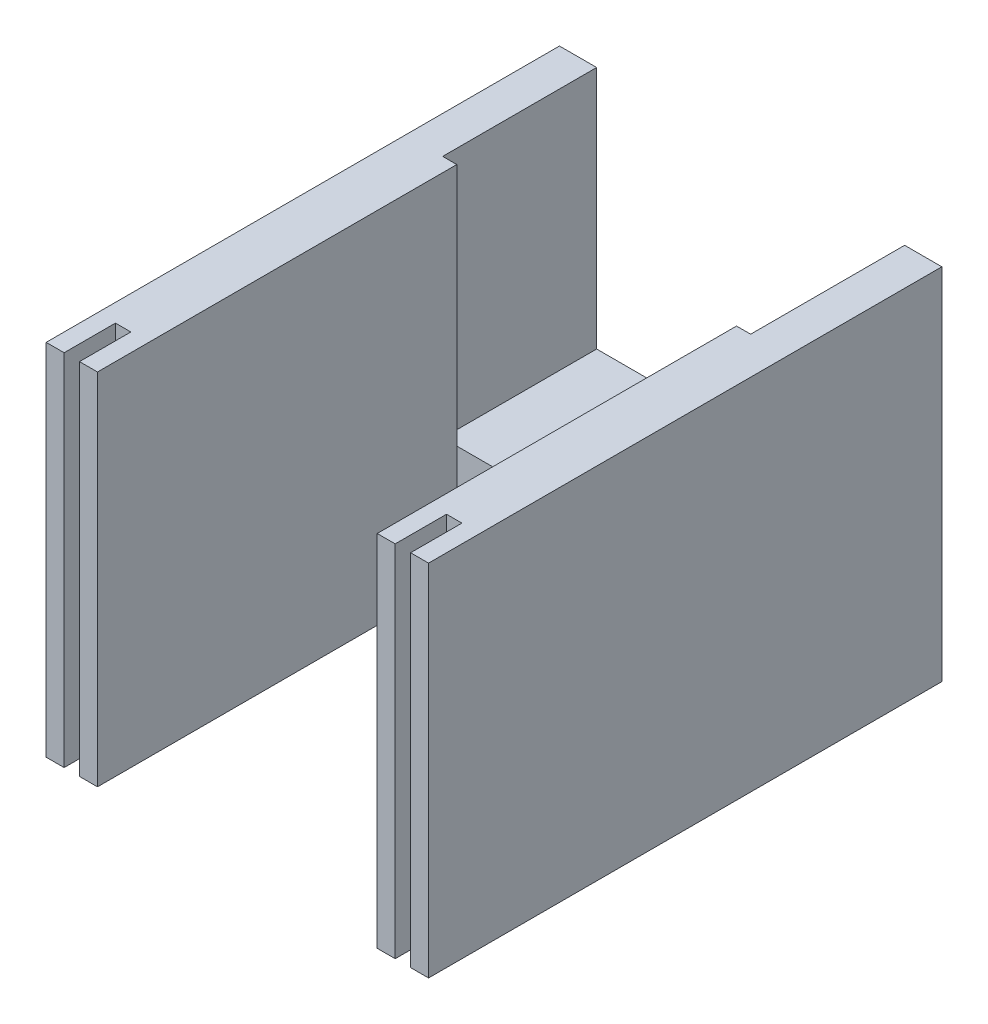
SolidWorks part; units mm, degrees
ref_plane "Front Plane" through (0, 0, 0) normal (0, 0, 1) x (1, 0, 0)
ref_plane "Top Plane" through (0, 0, 0) normal (0, 1, 0) x (1, 0, 0)
ref_plane "Right Plane" through (0, 0, 0) normal (1, 0, 0) x (0, 0, -1)
sketch "Sketch1" plane through (0, 0, 0) normal (0, 1, 0) x (1, 0, 0)
  line L1 (0, 0) -> (74.5, 0)
  line L2 (0, 0) -> (0, 100)
  line L3 (0, 100) -> (74.5, 100)
  line L4 (74.5, 0) -> (74.5, 100)
extrude "Boss-Extrude1" add sketch "Sketch1" along normal blind 70 contours L2 L3 L4 L1
sketch "Sketch3" plane through (0, 70, 0) normal (0, 1, 0) x (1, 0, 0)
  line L0 (74.5, 0) -> (57.5, 0)
  line L1 (0, 0) -> (74.5, 0) construction
  line L2 (0, 0) -> (10, 0)
  line L3 (0, 0) -> (10, 0)
  line L9 (10, 0) -> (64.5, 0)
  line L10 (10, 0) -> (10, 70)
  line L11 (10, 70) -> (64.5, 70)
  line L12 (64.5, 0) -> (64.5, 70)
  point P11 (0, 0)
extrude "Cut-Extrude1" cut sketch "Sketch3" against normal through all
ref_plane "Plane1" through (0, 70, -100) normal (1, 0, 0) x (0, 0, -1)
sketch "Sketch5" plane through (0, 70, 0) normal (0, 1, 0) x (1, 0, 0)
  line L0 (74.5, 100) -> (67.25, 100)
  line L1 (0, 100) -> (74.5, 100) construction
  line L2 (0, 100) -> (7.25, 100)
  line L3 (67.25, 100) -> (7.25, 100)
  line L4 (67.25, 100) -> (67.25, 70)
  line L5 (67.25, 70) -> (7.25, 70)
  line L6 (7.25, 100) -> (7.25, 70)
  point P9 (66.7211, 70.8322)
  line M13 (74.5, 100) -> (0, 100)
extrude "Cut-Extrude2" cut sketch "Sketch5" against normal blind 47.5 contours L6 L5 L4 M13
sketch "Sketch6" plane through (0, 70, 0) normal (0, 1, 0) x (1, 0, 0)
  line L0 (74.5, 0) -> (71, 0)
  line L1 (64.5, 0) -> (74.5, 0) construction
  line L2 (64.5, 0) -> (68, 0)
  line L4 (71, 0) -> (68, 0)
  line L5 (71, 0) -> (71, 10)
  line L6 (71, 10) -> (68, 10)
  line L7 (68, 0) -> (68, 10)
  line M11 (64.5, 0) -> (74.5, 0)
extrude "Cut-Extrude3" cut sketch "Sketch6" against normal through all contours L7 L5 L6 M11
sketch "Sketch7" plane through (0, 70, 0) normal (0, 1, 0) x (1, 0, 0)
  line L0 (10, 0) -> (6.5, 0)
  line L1 (0, 0) -> (10, 0) construction
  line L2 (0, 0) -> (3.5, 0)
  line L4 (6.5, 0) -> (3.5, 0)
  line L5 (6.5, 0) -> (6.5, 10)
  line L6 (6.5, 10) -> (3.5, 10)
  line L7 (3.5, 0) -> (3.5, 10)
  line M12 (0, 0) -> (10, 0)
extrude "Cut-Extrude4" cut sketch "Sketch7" against normal through all contours L7 L5 L6 M12
ref_plane "Plane2" through (64.5, 0, -70) normal (1, 0, 0) x (0, 0, -1)
sketch "Sketch10" plane through (0, 0, -100) normal (0, 0, -1) x (-1, 0, 0)
  line L0 (0, 0) -> (-74.5, 0) construction
  line L1 (-61.366, 0) -> (-10.6952, 0)
  line L2 (-61.366, 0) -> (-61.366, 10)
  line L3 (-61.366, 10) -> (-10.6952, 10)
  line L4 (-10.6952, 0) -> (-10.6952, 10)
extrude "Cut-Extrude5" cut sketch "Sketch10" against normal through all contours L3 L4 L1 L2
